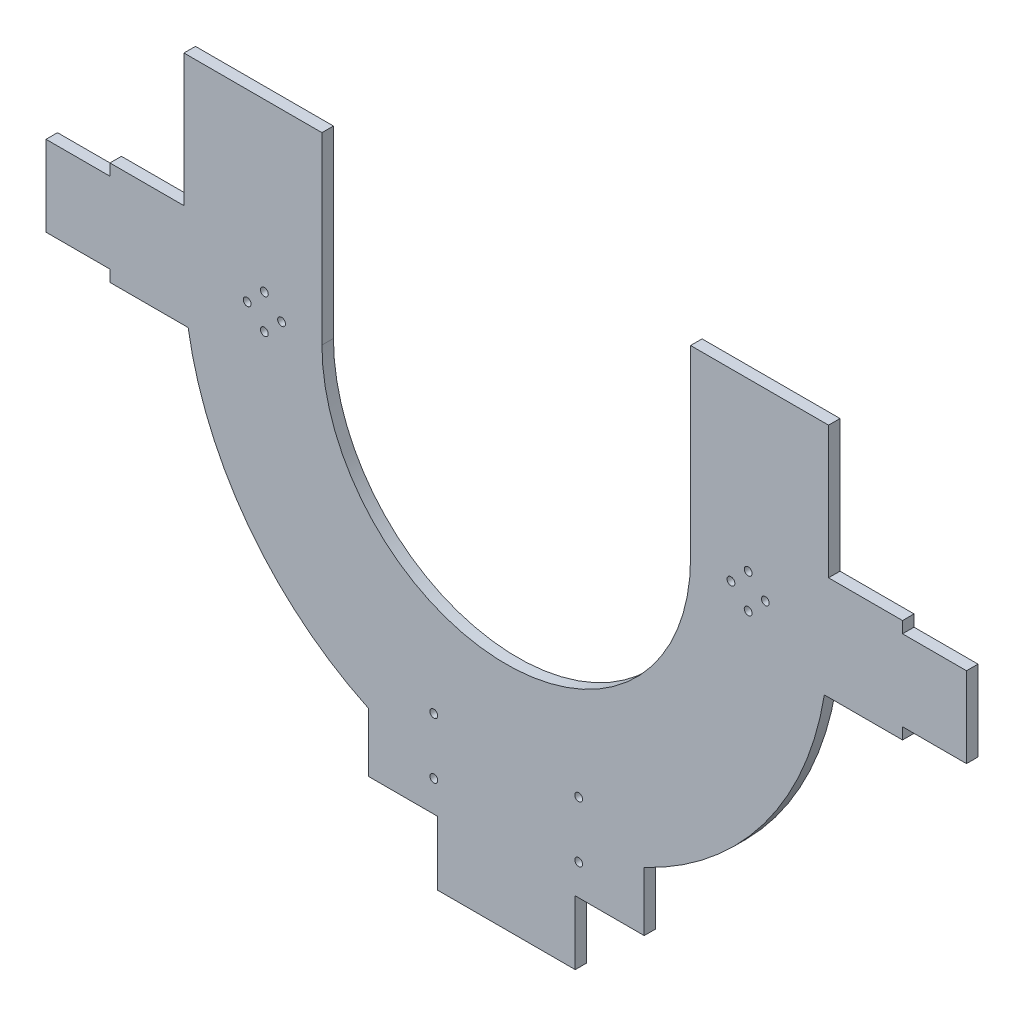
SolidWorks part; units mm, degrees
ref_plane "Front Plane" through (0, 0, 0) normal (0, 0, 1) x (1, 0, 0)
ref_plane "Top Plane" through (0, 0, 0) normal (0, 1, 0) x (1, 0, 0)
ref_plane "Right Plane" through (0, 0, 0) normal (1, 0, 0) x (0, 0, -1)
sketch "Sketch1" plane through (0, 0, 0) normal (0, 0, 1) x (1, 0, 0)
  line L0 (0, 53.4229) -> (0, -157.3867) construction
  line L1 (-101.8, 0) -> (-101.8, 101.6)
  line L2 (101.8, 0) -> (101.8, 101.6)
  line L11 (-101.8, 101.6) -> (-178, 101.6)
  line L12 (101.8, 101.6) -> (178, 101.6)
  line L13 (-178, 101.6) -> (-178, 28.575)
  line L14 (178, 101.6) -> (178, 28.575)
  line L15 (-178, 28.575) -> (-218.875, 28.575)
  line L16 (178, 28.575) -> (218.875, 28.575)
  line L17 (-218.875, 28.575) -> (-218.875, 22.225)
  line L18 (218.875, 28.575) -> (218.875, 22.225)
  line L19 (-218.875, 22.225) -> (-254.2, 22.225)
  line L20 (218.875, 22.225) -> (254.2, 22.225)
  line L21 (-254.2, 22.225) -> (-254.2, -22.225)
  line L22 (254.2, 22.225) -> (254.2, -22.225)
  line L23 (-254.2, -22.225) -> (-218.875, -22.225)
  line L24 (254.2, -22.225) -> (218.875, -22.225)
  line L25 (-218.875, -22.225) -> (-218.875, -28.575)
  line L26 (218.875, -22.225) -> (218.875, -28.575)
  line L27 (-218.875, -28.575) -> (-175.6914, -28.575)
  line L28 (218.875, -28.575) -> (175.6914, -28.575)
  line L33 (-76.2, -160.865) -> (-76.2, -193.475)
  line L34 (76.2, -160.865) -> (76.2, -193.475)
  line L36 (-76.2, -193.475) -> (-38.1, -193.475)
  line L37 (76.2, -193.475) -> (38.1, -193.475)
  line L38 (-38.1, -193.475) -> (-38.1, -228.8)
  line L39 (38.1, -193.475) -> (38.1, -228.8)
  line L40 (-38.1, -228.8) -> (38.1, -228.8)
  arc A1 (-101.8, 0) -> (101.8, 0) centre (0, 0) ccw
  arc A2 (-175.6914, -28.575) -> (-76.2, -160.865) centre (0, 0) ccw
  arc A3 (175.6914, -28.575) -> (76.2, -160.865) centre (0, 0) cw
  point P35 (0, -228.8)
  point P43 (-254.2, 0)
  dimension "D1" = 101.8
  dimension "D3" = 35.325
  dimension "D2" = 76.2
  dimension "D5" = 44.45
  dimension "D6" = 57.15
  dimension "D4" = 76.2
  dimension "D8" = 152.4
  dimension "D9" = 76.2
  dimension "D10" = 35.325
  dimension "D14" = 101.6
  dimension "D7" = 437.75
  dimension "D11" = 330.4
extrude "Boss-Extrude1" add sketch "Sketch1" along normal mid plane 6.35
sketch "Sketch2" plane through (0, 0, 3.175) normal (0, 0, 1) x (1, 0, 0)
  line L0 (-76.2, -160.865) -> (-76.2, -193.475) construction
  line L1 (-10.795, -217.17) -> (10.795, -217.17) construction
  line L2 (-10.795, -217.17) -> (-10.795, -137.17) construction
  line L3 (-10.795, -137.17) -> (10.795, -137.17) construction
  line L4 (10.795, -217.17) -> (10.795, -137.17) construction
  line L5 (-10.795, -217.17) -> (10.795, -137.17) construction
  line L6 (-10.795, -137.17) -> (10.795, -217.17) construction
  circle A1 centre (-10.795, -137.17) radius 2.159
  circle A2 centre (10.795, -137.17) radius 2.159
  circle A3 centre (-10.795, -217.17) radius 2.159
  circle A4 centre (10.795, -217.17) radius 2.159
  point P0 (0, -177.17)
  point P9 (-76.2, -177.17)
  point P13 (-10.795, -177.17)
  dimension "D3" = 4.318
  dimension "D1" = 80
  dimension "D2" = 21.59
extrude "Cut-Extrude1" [suppressed] cut sketch "Sketch2" against normal through all and the other way through all
sketch "Sketch3" plane through (0, 0, 3.175) normal (0, 0, 1) x (1, 0, 0)
  line L0 (0, 102.3984) -> (0, -397.5939) construction
  line L1 (-133.6, 9.5) -> (-133.6, -9.5) construction
  line L2 (-143.1, 0) -> (-124.1, 0) construction
  line L3 (143.1, 0) -> (124.1, 0) construction
  line L4 (133.6, 9.5) -> (133.6, -9.5) construction
  circle A0 centre (-133.6, 9.5) radius 2.1525
  circle A1 centre (-124.1, 0) radius 2.1525
  circle A2 centre (-143.1, 0) radius 2.1525
  circle A3 centre (-133.6, -9.5) radius 2.1525
  circle A4 centre (133.6, -9.5) radius 2.1525
  circle A5 centre (143.1, 0) radius 2.1525
  circle A6 centre (124.1, 0) radius 2.1525
  circle A7 centre (133.6, 9.5) radius 2.1525
  point P7 (-133.6, 0)
  point P8 (-133.6, 0)
  dimension "D3" = 4.305
  dimension "D1" = 19
  dimension "D2" = 19
  dimension "D4" = 248.2
extrude "Cut-Extrude2" cut sketch "Sketch3" against normal through all
sketch "Sketch4" plane through (0, 0, 0) normal (0, 0, 1) x (1, 0, 0)
  line L0 (-76.2, -160.865) -> (76.2, -160.865) construction
  line L1 (-40, -176.365) -> (40, -176.365) construction
  line L2 (-40, -176.365) -> (-40, -145.365) construction
  line L3 (-40, -145.365) -> (40, -145.365) construction
  line L4 (40, -176.365) -> (40, -145.365) construction
  line L5 (-40, -176.365) -> (40, -145.365) construction
  line L6 (-40, -145.365) -> (40, -176.365) construction
  circle A0 centre (40, -145.365) radius 2.159
  circle A1 centre (-40, -145.365) radius 2.159
  circle A2 centre (-40, -176.365) radius 2.159
  circle A3 centre (40, -176.365) radius 2.159
  point P0 (0, -160.865)
  dimension "D4" = 4.318
  dimension "D1" = 31
  dimension "D2" = 80
extrude "Cut-Extrude3" cut sketch "Sketch4" against normal through all and the other way through all
sketch "Sketch5" [suppressed] plane through (0, 0, 0) normal (0, 0, 1) x (1, 0, 0)
  line L1 (-22.5, -174.9) -> (22.5, -174.9) construction
  line L2 (-22.5, -174.9) -> (-22.5, -129.9) construction
  line L3 (-22.5, -129.9) -> (22.5, -129.9) construction
  line L4 (22.5, -174.9) -> (22.5, -129.9) construction
  line L5 (-22.5, -174.9) -> (22.5, -129.9) construction
  line L6 (-22.5, -129.9) -> (22.5, -174.9) construction
  line L7 (1, -138.4) -> (-9, -138.4)
  line L8 (1, -138.4) -> (1, -144.4)
  line L9 (1, -144.4) -> (-9, -144.4)
  line L10 (-9, -138.4) -> (-9, -144.4)
  line L11 (-14, -166.4) -> (14, -166.4) construction
  line L12 (-14, -166.4) -> (-14, -138.4) construction
  line L13 (-14, -138.4) -> (14, -138.4) construction
  line L14 (14, -166.4) -> (14, -138.4) construction
  line L15 (-14, -166.4) -> (14, -138.4) construction
  line L16 (-14, -138.4) -> (14, -166.4) construction
  circle A0 centre (-22.5, -129.9) radius 1.8
  circle A1 centre (22.5, -129.9) radius 1.8
  circle A2 centre (22.5, -174.9) radius 1.8
  circle A3 centre (-22.5, -174.9) radius 1.8
  point P0 (0, -152.4)
  point P9 (0, -152.4)
  dimension "D2" = 3.6
  dimension "D3" = 152.4
  dimension "D1" = 45
  dimension "D4" = 6
  dimension "D5" = 10
  dimension "D7" = 28
  dimension "D6" = 5
extrude "Cut-Extrude4" [suppressed] cut sketch "Sketch5" against normal through all and the other way through all contours A0 | A1 | A3 | A2 | L9 L10 L7 L8
sketch "Sketch6" [suppressed] plane through (0, 0, 3.175) normal (0, 0, 1) x (1, 0, 0)
  line L0 (0, -155.6) -> (-9.5, -165.1) construction
  line L1 (-9.5, -165.1) -> (0, -174.6) construction
  line L2 (0, -174.6) -> (9.5, -165.1) construction
  line L3 (9.5, -165.1) -> (0, -155.6) construction
  line L4 (0, -155.6) -> (0, -174.6) construction
  circle A0 centre (0, -155.6) radius 1.8
  circle A1 centre (-9.5, -165.1) radius 1.8
  circle A2 centre (0, -174.6) radius 1.8
  circle A3 centre (9.5, -165.1) radius 1.8
  point P7 (0, -165.1)
  dimension "D2" = 19
  dimension "D3" = 3.6
  dimension "D1" = 165.1
extrude "Cut-Extrude5" [suppressed] cut sketch "Sketch6" against normal through all
equation "\"tube diameter\"= 8in"
equation "\"tolerance\"= .2mm"
equation "\"D1@Sketch1\"=(\"tube diameter\" + (2*\"tolerance\"))/2"
equation "\"outside pc tube\"= 1.375in"
equation "\"D3@Sketch1\"=\"outside pc tube\"+(2*\"tolerance\")"
equation "\"D10@Sketch1\"=\"outside pc tube\"+(2*\"tolerance\")"
equation "\"D14@Sketch1\"=\"tube diameter\"/2"
equation "\"total width\"= 20in"
equation "\"sheet thickness\"= .25in"
equation "\"D1@Boss-Extrude1\"=\"sheet thickness\""
equation "\"manipulator holes\"= .17in"
equation "\"D3@Sketch2\"=\"manipulator holes\""
equation "\"flange holes\"= 4.305mm"
equation "\"D3@Sketch3\"=\"flange holes\""
equation "\"D7@Sketch1\"=\"total width\"-(2*\"tolerance\")-(\"outside pc tube\"*2)"
equation "\"D4@Sketch4\"=\"manipulator holes\""
equation "\"total height\"= 13in"
equation "\"D11@Sketch1\"=\"total height\"+\"tolerance\""
equation "\"camera mount holes\"= 3.6mm"
equation "\"D2@Sketch5\"=\"camera mount holes\""
equation "\"D3@Sketch6\"=\"camera mount holes\""
